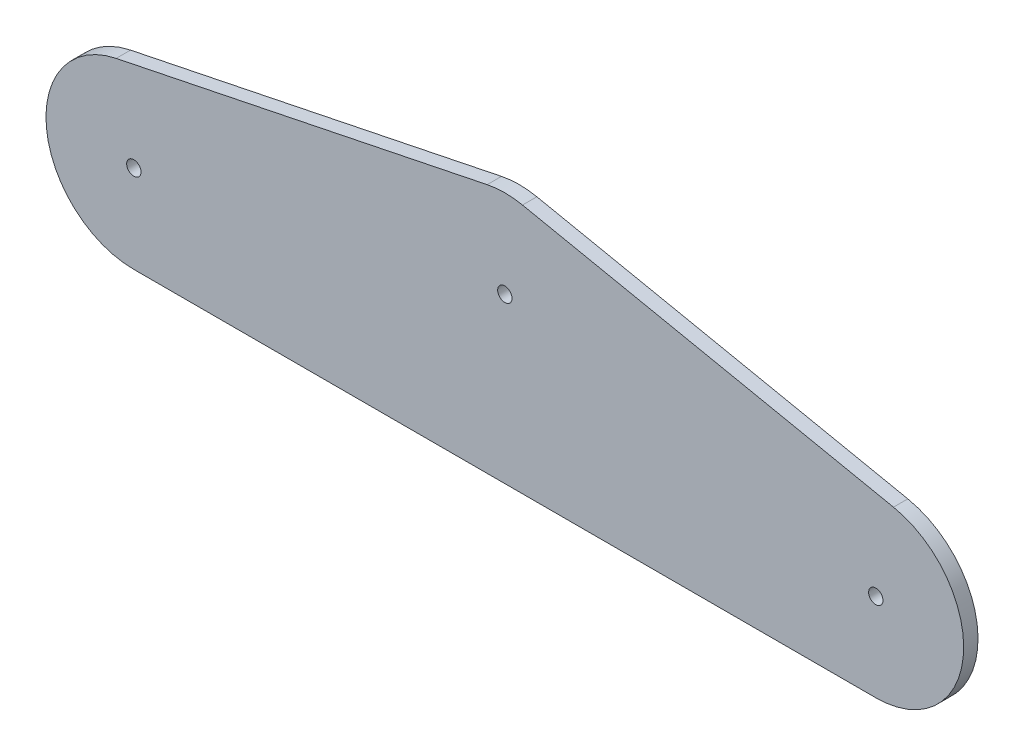
SolidWorks part; units mm, degrees
ref_plane "Front Plane" through (0, 0, 0) normal (0, 0, 1) x (1, 0, 0)
ref_plane "Top Plane" through (0, 0, 0) normal (0, 1, 0) x (1, 0, 0)
ref_plane "Right Plane" through (0, 0, 0) normal (1, 0, 0) x (0, 0, -1)
sketch "Sketch1" plane through (0, 0, 0) normal (0, 0, 1) x (1, 0, 0)
  line L0 (0, 109.8086) -> (0, -102.0697) construction
  line L1 (0, 0) -> (-160.8667, 0)
  line L2 (0, 0) -> (0, 33.02)
  line L3 (168.5275, 37.3219) -> (7.6608, 70.3419)
  line L5 (-168.5275, 37.3219) -> (-7.6608, 70.3419)
  line L6 (-160.8667, -38.1) -> (160.8667, -38.1)
  circle A0 centre (-160.8667, 0) radius 3.1115
  circle A1 centre (0, 33.02) radius 3.1115
  circle A2 centre (-160.8667, 0) radius 38.1
  circle A3 centre (0, 33.02) radius 38.1
  circle A4 centre (160.8667, 0) radius 3.1115
  circle A5 centre (160.8667, 0) radius 38.1
  point P17 (0, -38.1)
  dimension "D3" = 6.223
  dimension "D4" = 6.223
  dimension "D5" = 76.2
  dimension "D6" = 76.2
  dimension "D1" = 33.02
  dimension "D2" = 160.8667
extrude "Boss-Extrude1" add sketch "Sketch1" along normal blind 6.223
